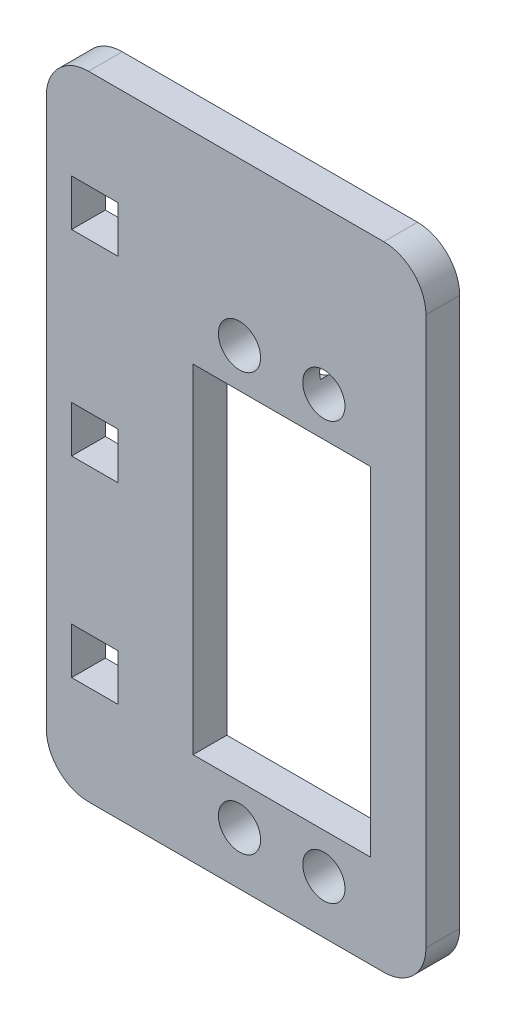
SolidWorks part; units mm, degrees
ref_plane "前视基准面" through (0, 0, 0) normal (0, 0, 1) x (1, 0, 0)
ref_plane "上视基准面" through (0, 0, 0) normal (0, 1, 0) x (1, 0, 0)
ref_plane "右视基准面" through (0, 0, 0) normal (1, 0, 0) x (0, 0, -1)
sketch "草图4" plane through (0, 0, 0) normal (0, 0, 1) x (1, 0, 0)
  line L0 (-30.5142, -31.0858) -> (-0.5142, -31.0858)
  line L5 (-0.5142, -31.0858) -> (-0.5142, 43.9142)
  line L6 (-0.5142, 43.9142) -> (-30.5142, 43.9142)
  line L12 (-7.1142, -20.0508) -> (-7.1142, 20.0492)
  line L18 (-28.1142, 20.0492) -> (-28.1142, -20.0508)
  line L32 (-7.1142, 20.0492) -> (-28.1142, 20.0492)
  line L33 (-30.5142, 43.9142) -> (-45.5142, 43.9142)
  line L35 (-30.5142, -31.0858) -> (-45.5142, -31.0858)
  line L36 (-45.5142, 43.9142) -> (-45.5142, -31.0858)
  line L37 (-7.1142, -20.0508) -> (-28.1142, -20.0508)
  circle A2 centre (-22.6142, 24.6992) radius 2.5
  circle A3 centre (-12.6142, 24.6992) radius 2.5
  circle A4 centre (-12.6142, -24.8008) radius 2.5
  circle A5 centre (-22.6142, -24.8008) radius 2.5
  dimension "D3" = 5
  dimension "D1" = 75
  dimension "D2" = 28.1142
  dimension "D4" = 7.1142
  dimension "D5" = 12.6142
  dimension "D6" = 20.0508
  dimension "D8" = 22.6142
  dimension "D9" = 20.0492
  dimension "D10" = 24.6992
  dimension "D13" = 24.8008
extrude "凸台-拉伸1" add sketch "草图4" along normal blind 4
sketch "草图5" plane through (0, 0, 0) normal (0, 0, -1) x (-1, 0, 0)
  line L0 (45.5142, 43.9142) -> (42.5142, 43.9142)
  line L1 (0.5142, 43.9142) -> (45.5142, 43.9142) construction
  line L2 (42.5142, 43.9142) -> (42.5142, -31.0858) construction
  line L3 (45.5142, -31.0858) -> (0.5142, -31.0858) construction
  line L4 (42.5142, -31.0858) -> (37.0142, -31.0858) construction
  line L5 (37.0142, -31.0858) -> (37.0142, 43.9142) construction
  line L6 (37.0142, 43.9142) -> (42.5142, 43.9142) construction
  line L7 (37.0142, 43.9142) -> (37.0142, 32.1642) construction
  line L8 (37.0142, 32.1642) -> (42.5142, 32.1642)
  line L9 (42.5142, 32.1642) -> (42.5142, 26.6642)
  line L10 (42.5142, 26.6642) -> (37.0142, 26.6642)
  line L11 (37.0142, 26.6642) -> (37.0142, 32.1642)
  line L12 (42.5142, 6.4142) -> (42.5142, 8.9142)
  line L13 (42.5142, 8.9142) -> (37.0142, 8.9142)
  line L14 (37.0142, 8.9142) -> (37.0142, 3.4142)
  line L15 (37.0142, 3.4142) -> (42.5142, 3.4142)
  line L16 (42.5142, 3.4142) -> (42.5142, 8.9142)
  line L17 (37.0142, -31.0858) -> (37.0142, -19.3358)
  line L18 (37.0142, -19.3358) -> (42.5142, -19.3358)
  line L19 (42.5142, -19.3358) -> (42.5142, -13.8358)
  line L20 (42.5142, -13.8358) -> (37.0142, -13.8358)
  line L21 (37.0142, -13.8358) -> (37.0142, -19.3358)
  dimension "D1" = 3
  dimension "D2" = 5.5
  dimension "D3" = 11.75
  dimension "D4" = 5.5
  dimension "D5" = 2.5
  dimension "D6" = 5.5
  dimension "D7" = 11.75
  dimension "D8" = 5.5
extrude "切除-拉伸5" cut sketch "草图5" against normal blind 10 contours L15 L16 L12 L13 L14 | L11 L10 L9 L8 | L20 L21 L18 L19
fillet "圆角1" radius 5 4 edges at (-45.5142, 43.9142, 2) (-45.5142, -31.0858, 2) (-0.5142, -31.0858, 2) (-0.5142, 43.9142, 2)
sketch "草图6" plane through (0, 0, 0) normal (0, 0, -1) x (-1, 0, 0)
  line L0 (45.5142, 38.9142) -> (45.5142, -26.0858) construction
  line L1 (5.5142, 43.9142) -> (40.5142, 43.9142) construction
  circle A0 centre (17.6142, 25.5042) radius 3
  dimension "D1" = 27.9
  dimension "D2" = 18.41
extrude "切除-拉伸6" cut sketch "草图6" against normal blind 2
sketch "草图7" plane through (0, 0, 4) normal (0, 0, 1) x (1, 0, 0)
